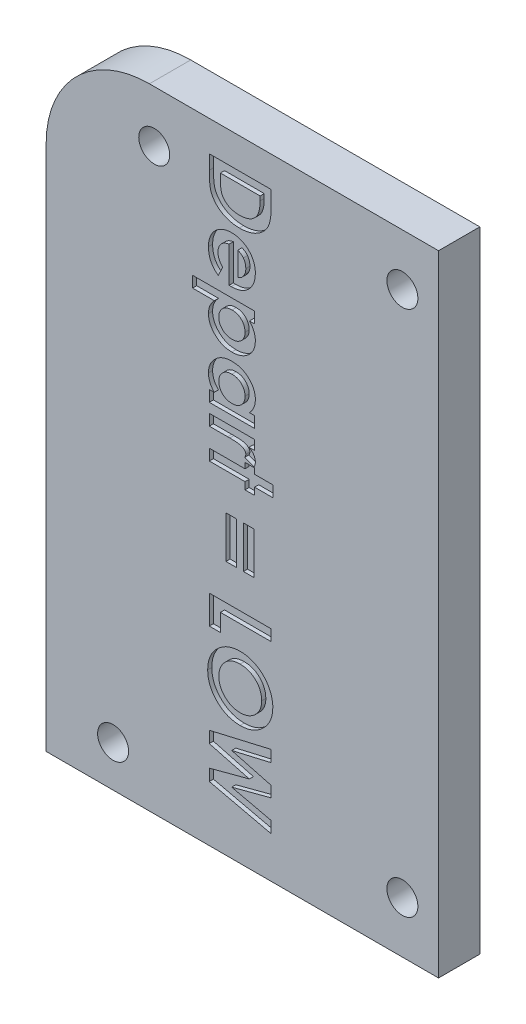
SolidWorks part; units mm, degrees
ref_plane "Plan de face" through (0, 0, 0) normal (0, 0, 1) x (1, 0, 0)
ref_plane "Plan de dessus" through (0, 0, 0) normal (0, 1, 0) x (1, 0, 0)
ref_plane "Plan de droite" through (0, 0, 0) normal (1, 0, 0) x (0, 0, -1)
sketch "Esquisse1" plane through (0, 0, 0) normal (0, 0, 1) x (1, 0, 0)
  line L1 (-19, -30.5) -> (19, -30.5)
  line L2 (-19, -30.5) -> (-19, 30.5)
  line L3 (-19, 30.5) -> (19, 30.5)
  line L4 (19, -30.5) -> (19, 30.5)
  line L5 (-19, -30.5) -> (19, 30.5) construction
  line L6 (-19, 30.5) -> (19, -30.5) construction
  point P0 (0, 0)
  dimension "D1" = 61
  dimension "D2" = 38
extrude "Boss.-Extru.1" add sketch "Esquisse1" along normal blind 4
sketch "Esquisse2" plane through (0, 0, 0) normal (0, 0, -1) x (-1, 0, 0)
  circle A0 centre (12.5169, -26.5) radius 1.5
  circle A1 centre (-15.5, -25.5) radius 1.5
  circle A2 centre (-15.5, 25.5) radius 1.5
  circle A3 centre (8.5339, 25.5) radius 1.5
  dimension "D1" = 3
extrude "Enlèv. mat.-Extru.1" cut sketch "Esquisse2" against normal blind 4
fillet "Congé1" radius 10 1 edges at (-19, 30.5, 2)
sketch "Esquisse3" plane through (0, 0, 4) normal (0, 0, 1) x (1, 0, 0)
  line L0 (-3.2032, 28.222) -> (-3.2032, -23.1128) construction
  text T0 "<b>Depart = LOW</b>" font "Century Gothic" height 6
extrude "Enlèv. mat.-Extru.2" cut sketch "Esquisse3" against normal blind 0.4
